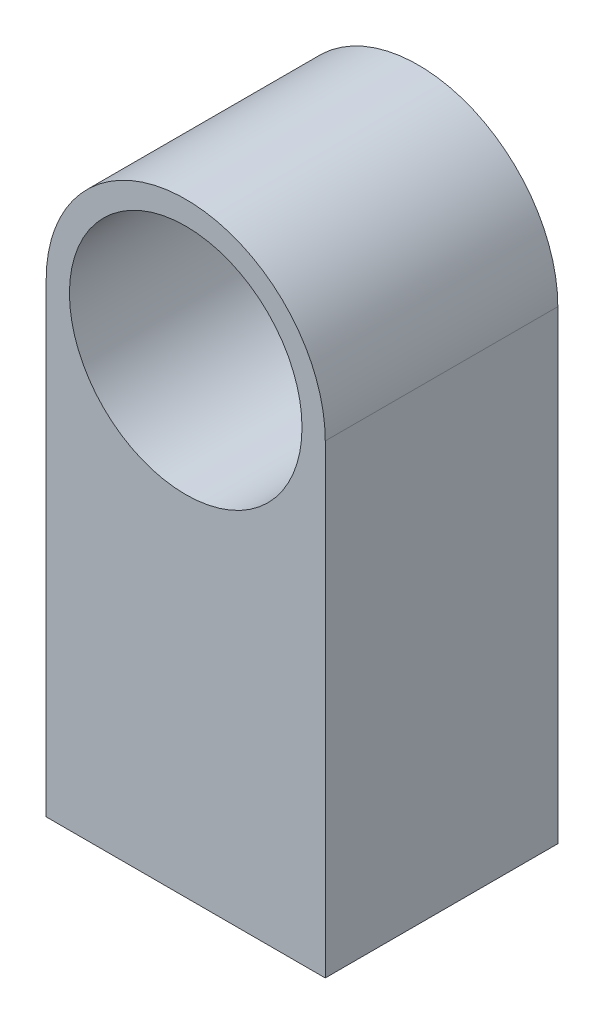
SolidWorks part; units mm, degrees
ref_plane "前视基准面" through (0, 0, 0) normal (0, 0, 1) x (1, 0, 0)
ref_plane "上视基准面" through (0, 0, 0) normal (0, 1, 0) x (1, 0, 0)
ref_plane "右视基准面" through (0, 0, 0) normal (1, 0, 0) x (0, 0, -1)
sketch "草图1" plane through (0, 0, 0) normal (0, 0, 1) x (1, 0, 0)
  line L2 (-51.2621, 98.0583) -> (-51.2621, -101.9417)
  line L3 (-51.2621, -101.9417) -> (68.7379, -101.9417)
  line L4 (68.7379, 98.0583) -> (68.7379, -101.9417)
  arc A0 (-51.2621, 98.0583) -> (68.7379, 98.0583) centre (8.7379, 98.0583) cw
  circle A1 centre (8.7379, 98.0583) radius 50
  dimension "D1" = 120
  dimension "D2" = 200
extrude "凸台-拉伸1" add sketch "草图1" along normal blind 100
sketch "草图2" plane through (0, -101.9417, 0) normal (0, -1, 0) x (-1, 0, 0)
  circle A0 centre (-8.7379, -52.2483) radius 6.693
extrude "切除-拉伸1" cut sketch "草图2" against normal blind 5
